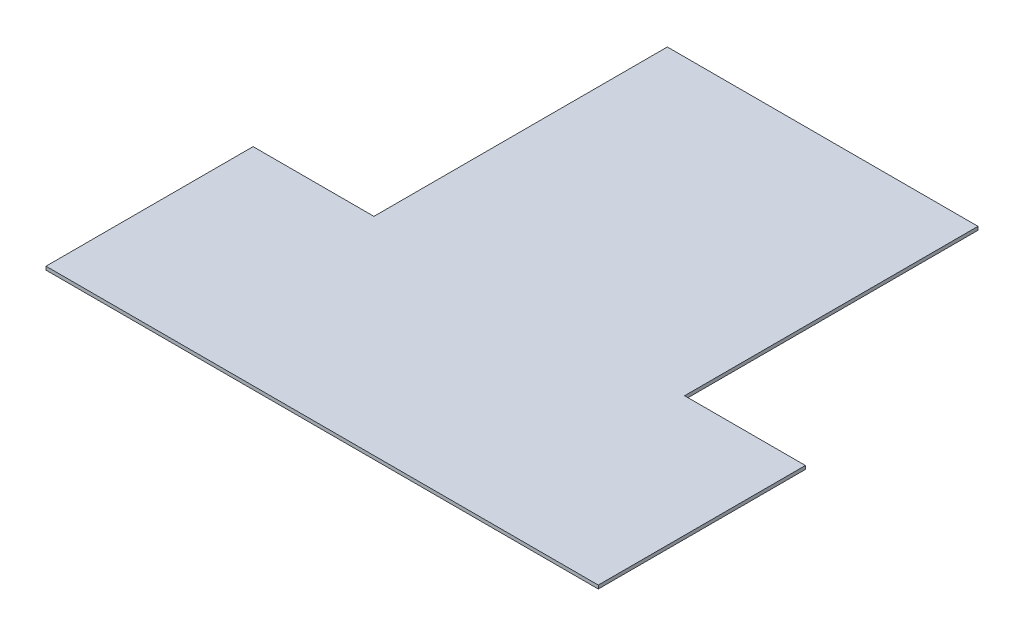
SolidWorks part; units mm, degrees
material "5052-H32"
ref_plane "Front" through (0, 0, 0) normal (0, 0, 1) x (1, 0, 0)
ref_plane "Top" through (0, 0, 0) normal (0, 1, 0) x (1, 0, 0)
ref_plane "Right" through (0, 0, 0) normal (1, 0, 0) x (0, 0, -1)
sketch "Sketch1" plane through (0, 0, 0) normal (0, 1, 0) x (1, 0, 0)
  line L0 (-45.9969, -156.7777) -> (-45.9969, 59.1223)
  line L1 (-45.9969, 59.1223) -> (182.6031, 59.1223)
  line L2 (182.6031, 59.1223) -> (182.6031, -156.7777)
  line L3 (182.6031, -156.7777) -> (271.5031, -156.7777)
  line L4 (271.5031, -156.7777) -> (271.5031, -309.1777)
  line L5 (271.5031, -309.1777) -> (-134.8969, -309.1777)
  line L6 (-134.8969, -309.1777) -> (-134.8969, -156.7777)
  line L7 (-134.8969, -156.7777) -> (-45.9969, -156.7777)
  dimension "D1" = 88.9
  dimension "D2" = 88.9
  dimension "D3" = 228.6
  dimension "D4" = 215.9
  dimension "D5" = 215.9
  dimension "D6" = 152.4
  dimension "D7" = 152.4
  dimension "D8" = 406.4
extrude "Extrude1" add sketch "Sketch1" along normal blind 2.54
